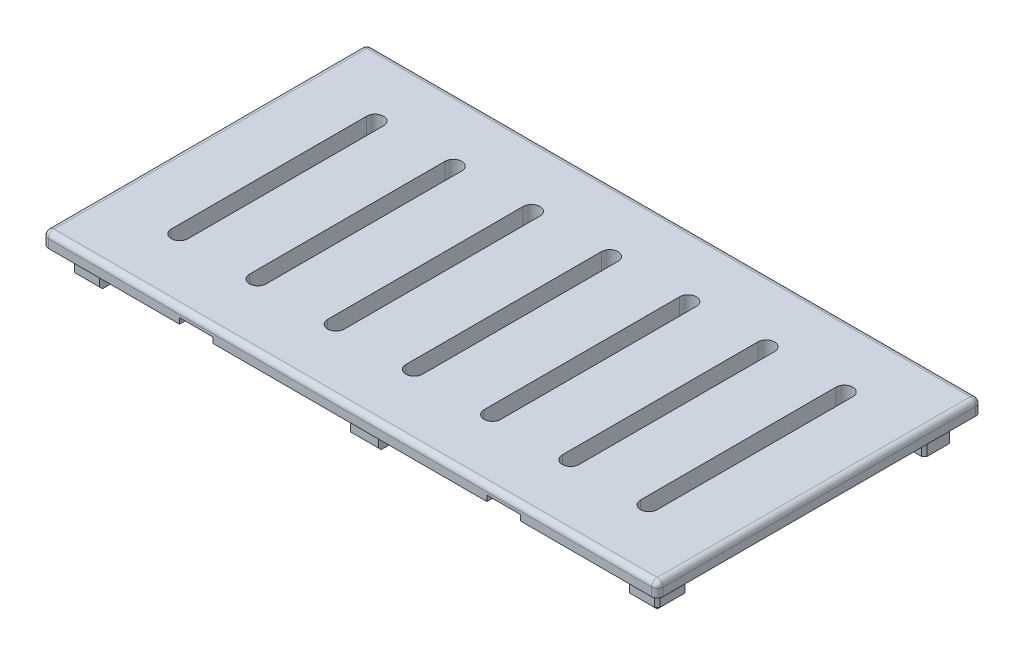
SolidWorks part; units mm, degrees
ref_plane "Front Plane" through (0, 0, 0) normal (0, 0, 1) x (1, 0, 0)
ref_plane "Top Plane" through (0, 0, 0) normal (0, 1, 0) x (1, 0, 0)
ref_plane "Right Plane" through (0, 0, 0) normal (1, 0, 0) x (0, 0, -1)
sketch "Sketch1" plane through (0, 0, 0) normal (0, 1, 0) x (1, 0, 0)
  line L1 (0, 0) -> (110, 0)
  line L2 (0, 0) -> (0, 58)
  line L3 (0, 58) -> (110, 58)
  line L4 (110, 0) -> (110, 58)
  dimension "D1" = 110
  dimension "D2" = 58
extrude "Boss-Extrude1" add sketch "Sketch1" along normal blind 2.5
sketch "Sketch2" plane through (0, 0, 0) normal (0, -1, 0) x (1, 0, 0)
  line L0 (0, -58) -> (0, 0) construction
  line L1 (2.6, -55.4) -> (107.4, -55.4)
  line L2 (2.6, -55.4) -> (2.6, -2.6)
  line L3 (2.6, -2.6) -> (107.4, -2.6)
  line L4 (107.4, -55.4) -> (107.4, -2.6)
  line L5 (0, 0) -> (110, 0) construction
  line L6 (110, 0) -> (110, -58) construction
  line L7 (110, -58) -> (0, -58) construction
  point P10 (-3.8988, -0.6044)
  point P12 (20.574, 3.4939)
  dimension "D1" = 2.6
  dimension "D2" = 2.6
  dimension "D3" = 2.6
  dimension "D4" = 2.6
extrude "Boss-Extrude2" add sketch "Sketch2" along normal blind 1.5
sketch "Sketch3" plane through (0, -1.5, 0) normal (0, -1, 0) x (1, 0, 0)
  line L0 (55, -4.6) -> (55, -55.4) construction
  line L2 (2.6, -55.4) -> (107.4, -55.4) construction
  line L3 (107.4, -29) -> (2.6, -29) construction
  line L4 (107.4, -55.4) -> (107.4, -2.6) construction
  line L5 (2.6, -2.6) -> (2.6, -55.4) construction
  line L6 (57.5, -2.6) -> (57.5, -4.6)
  line L7 (2.6, -2.6) -> (7.6, -2.6)
  line L8 (2.6, -2.6) -> (2.6, -7.6)
  line L9 (2.6, -7.6) -> (4.6, -7.6)
  line L10 (7.6, -2.6) -> (7.6, -4.6)
  line L13 (7.6, -4.6) -> (4.6, -4.6)
  line L14 (4.6, -7.6) -> (4.6, -4.6)
  line L15 (57.5, -2.6) -> (52.5, -2.6)
  line L17 (57.5, -4.6) -> (52.5, -4.6)
  line L18 (52.5, -2.6) -> (52.5, -4.6)
  line L19 (107.4, -2.6) -> (107.4, -7.6)
  line L20 (107.4, -7.6) -> (105.4, -7.6)
  line L21 (105.4, -7.6) -> (105.4, -4.6)
  line L22 (102.4, -4.6) -> (105.4, -4.6)
  line L23 (102.4, -2.6) -> (102.4, -4.6)
  line L24 (107.4, -2.6) -> (102.4, -2.6)
  line L25 (107.4, -55.4) -> (102.4, -55.4)
  line L26 (102.4, -55.4) -> (102.4, -53.4)
  line L27 (102.4, -53.4) -> (105.4, -53.4)
  line L28 (105.4, -50.4) -> (105.4, -53.4)
  line L29 (107.4, -50.4) -> (105.4, -50.4)
  line L30 (107.4, -55.4) -> (107.4, -50.4)
  line L31 (57.5, -55.4) -> (57.5, -53.4)
  line L32 (57.5, -55.4) -> (52.5, -55.4)
  line L33 (52.5, -55.4) -> (52.5, -53.4)
  line L34 (57.5, -53.4) -> (52.5, -53.4)
  line L35 (2.6, -55.4) -> (2.6, -50.4)
  line L36 (2.6, -50.4) -> (4.6, -50.4)
  line L37 (4.6, -50.4) -> (4.6, -53.4)
  line L38 (7.6, -53.4) -> (4.6, -53.4)
  line L39 (7.6, -55.4) -> (7.6, -53.4)
  line L40 (2.6, -55.4) -> (7.6, -55.4)
  dimension "D1" = 5
  dimension "D2" = 5
  dimension "D3" = 2
  dimension "D4" = 2
  dimension "D6" = 2
extrude "Boss-Extrude3" add sketch "Sketch3" along normal blind 3
fillet "Fillet1" radius 1 4 edges at (4.6, -3, -53.4) (105.4, -3, -53.4) (105.4, -3, -4.6) (4.6, -3, -4.6)
sketch "Sketch4" plane through (0, 0, 0) normal (0, -1, 0) x (1, 0, 0)
  line L0 (55, 0) -> (55, -58) construction
  line L1 (0, 0) -> (110, 0) construction
  line L2 (110, -58) -> (0, -58) construction
  line L3 (0, -29) -> (55, -29) construction
  line L4 (0, -58) -> (0, 0) construction
  line L6 (27.5, -29) -> (27.5, -2.6) construction
  line L7 (107.4, -2.6) -> (2.6, -2.6) construction
  line L8 (30.5, 0) -> (24.5, 0)
  line L10 (30.5, -2.6) -> (24.5, -2.6)
  line L11 (24.5, 0) -> (24.5, -2.6)
  line L12 (30.5, 0) -> (30.5, -2.6)
  line L13 (79.5, 0) -> (79.5, -2.6)
  line L14 (79.5, 0) -> (85.5, 0)
  line L15 (85.5, 0) -> (85.5, -2.6)
  line L16 (79.5, -2.6) -> (85.5, -2.6)
  line L17 (79.5, -58) -> (85.5, -58)
  line L18 (85.5, -58) -> (85.5, -55.4)
  line L19 (79.5, -55.4) -> (85.5, -55.4)
  line L20 (79.5, -58) -> (79.5, -55.4)
  line L21 (30.5, -58) -> (30.5, -55.4)
  line L22 (30.5, -58) -> (24.5, -58)
  line L23 (24.5, -58) -> (24.5, -55.4)
  line L24 (30.5, -55.4) -> (24.5, -55.4)
extrude "Cut-Extrude1" cut sketch "Sketch4" against normal blind 1
fillet "Fillet2" radius 1 4 edges at (0, 1.25, -58) (0, 1.25, 0) (110, 1.25, -58) (110, 1.25, 0)
chamfer "Chamfer1" distance 0.5 angle 45 14 edges at (55, -4.5, -55.4) (2.6, -3, -50.4) (2.6, -2.25, -55.4) (7.6, -3, -55.4) (107.4, -3, -50.4) (102.4, -3, -55.4) (107.4, -2.25, -55.4) (107.4, -2.25, -2.6) (107.4, -4.5, -5.1) (104.9, -4.5, -2.6) (55, -4.5, -2.6) (2.6, -4.5, -5.1) (5.1, -4.5, -2.6) (2.6, -2.25, -2.6)
sketch "Sketch5" plane through (0, 2.5, 0) normal (0, 1, 0) x (1, 0, 0)
  line L0 (0, 29) -> (110, 29) construction
  line L1 (0, 57) -> (0, 1) construction
  line L2 (110, 1) -> (110, 57) construction
  line L3 (55, 58) -> (55, 0) construction
  line L4 (109, 58) -> (1, 58) construction
  line L5 (1, 0) -> (109, 0) construction
  line L6 (55, 46.5) -> (55, 11.5) construction
  line L7 (56.5, 46.5) -> (56.5, 11.5)
  line L8 (53.5, 46.5) -> (53.5, 11.5)
  line L9 (67.5, 46.5) -> (67.5, 11.5)
  line L10 (70.5, 46.5) -> (70.5, 11.5)
  line L11 (69, 46.5) -> (69, 11.5) construction
  line L12 (81.5, 46.5) -> (81.5, 11.5)
  line L13 (84.5, 46.5) -> (84.5, 11.5)
  line L14 (83, 46.5) -> (83, 11.5) construction
  line L15 (95.5, 46.5) -> (95.5, 11.5)
  line L16 (98.5, 46.5) -> (98.5, 11.5)
  line L17 (97, 46.5) -> (97, 11.5) construction
  line L18 (39.5, 46.5) -> (39.5, 11.5)
  line L19 (42.5, 46.5) -> (42.5, 11.5)
  line L20 (41, 46.5) -> (41, 11.5) construction
  line L21 (25.5, 46.5) -> (25.5, 11.5)
  line L22 (28.5, 46.5) -> (28.5, 11.5)
  line L23 (27, 46.5) -> (27, 11.5) construction
  line L24 (11.5, 46.5) -> (11.5, 11.5)
  line L25 (14.5, 46.5) -> (14.5, 11.5)
  line L26 (13, 46.5) -> (13, 11.5) construction
  arc A0 (56.5, 46.5) -> (53.5, 46.5) centre (55, 46.5) ccw
  arc A1 (53.5, 11.5) -> (56.5, 11.5) centre (55, 11.5) ccw
  arc A2 (70.5, 46.5) -> (67.5, 46.5) centre (69, 46.5) ccw
  arc A3 (67.5, 11.5) -> (70.5, 11.5) centre (69, 11.5) ccw
  arc A4 (84.5, 46.5) -> (81.5, 46.5) centre (83, 46.5) ccw
  arc A5 (81.5, 11.5) -> (84.5, 11.5) centre (83, 11.5) ccw
  arc A6 (98.5, 46.5) -> (95.5, 46.5) centre (97, 46.5) ccw
  arc A7 (95.5, 11.5) -> (98.5, 11.5) centre (97, 11.5) ccw
  arc A8 (42.5, 46.5) -> (39.5, 46.5) centre (41, 46.5) ccw
  arc A9 (39.5, 11.5) -> (42.5, 11.5) centre (41, 11.5) ccw
  arc A10 (28.5, 46.5) -> (25.5, 46.5) centre (27, 46.5) ccw
  arc A11 (25.5, 11.5) -> (28.5, 11.5) centre (27, 11.5) ccw
  arc A12 (14.5, 46.5) -> (11.5, 46.5) centre (13, 46.5) ccw
  arc A13 (11.5, 11.5) -> (14.5, 11.5) centre (13, 11.5) ccw
  point P14 (55, 29)
  point P23 (69, 29)
  point P30 (83, 29)
  point P37 (97, 29)
  point P43 (41, 29)
  point P50 (27, 29)
  point P57 (13, 29)
  dimension "D3" = 1.5
  dimension "D1" = 17.5
  dimension "D2" = 17.5
  dimension "D4" = 4
  dimension "D5" = 4
extrude "Cut-Extrude2" cut sketch "Sketch5" against normal through all
fillet "Fillet3" radius 1 8 edges at (0.2929, 2.5, -0.2929) (0, 2.5, -29) (0.2929, 2.5, -57.7071) (55, 2.5, -58) (109.7071, 2.5, -57.7071) (110, 2.5, -29) (109.7071, 2.5, -0.2929) (55, 2.5, 0)
